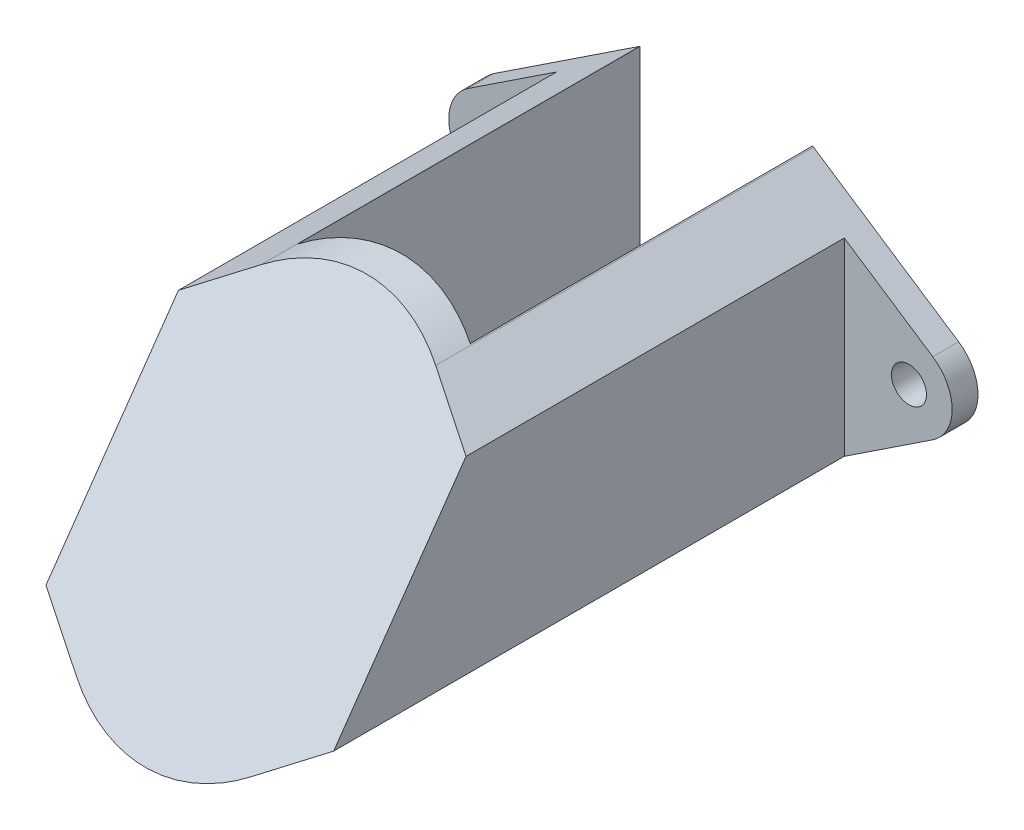
SolidWorks part; units mm, degrees
ref_plane "Front Plane" through (0, 0, 0) normal (0, 0, 1) x (1, 0, 0)
ref_plane "Top Plane" through (0, 0, 0) normal (0, 1, 0) x (1, 0, 0)
ref_plane "Right Plane" through (0, 0, 0) normal (1, 0, 0) x (0, 0, -1)
sketch "Sketch1" plane through (0, 0, 0) normal (0, 0, 1) x (1, 0, 0)
  line L0 (-14.5, 0) -> (14.5, 0) construction
  line L1 (-16.1552, 2.5021) -> (-6.069, 9.1743)
  line L2 (6.069, 9.1743) -> (16.1552, 2.5021)
  line L5 (16.1552, -2.5021) -> (6.069, -9.1743)
  line L6 (-6.069, -9.1743) -> (-16.1552, -2.5021)
  arc A0 (-6.069, -9.1743) -> (6.069, -9.1743) centre (0, 0) ccw
  arc A1 (16.1552, -2.5021) -> (16.1552, 2.5021) centre (14.5, 0) ccw
  arc A2 (-16.1552, 2.5021) -> (-16.1552, -2.5021) centre (-14.5, 0) ccw
  arc A3 (6.069, 9.1743) -> (-6.069, 9.1743) centre (0, 0) ccw
  point P1 (0, 0)
  point P4 (0, 0)
  point P6 (16.1552, -2.5021)
  dimension "D1" = 6
  dimension "D2" = 22
  dimension "D3" = 29
extrude "Boss-Extrude1" add sketch "Sketch1" along normal blind 45
sketch "Sketch3" plane through (0, 0, 0) normal (1, 0, 0) x (0, 0, -1)
  line L0 (-25, 11) -> (-40.4046, -11)
  line L1 (0, 11) -> (-45, 11) construction
  line L2 (-45, -11) -> (0, -11) construction
  line L3 (-40.4046, -11) -> (0, -11)
  line L4 (0, -11) -> (0, 11)
  line L5 (0, 11) -> (-25, 11)
  point P6 (-2.9931, 11)
  dimension "D1" = 35
  dimension "D2" = 25
extrude "Cut-Extrude1" cut sketch "Sketch3" against normal through all both and the other way through all flip side to cut
sketch "Sketch5" plane through (0, 0, 0) normal (0, 0, -1) x (-1, 0, 0)
  line L1 (-10, -12.207) -> (10, -12.207)
  line L2 (-10, -12.207) -> (-10, 12.207)
  line L3 (-10, 12.207) -> (10, 12.207)
  line L4 (10, -12.207) -> (10, 12.207)
  line L5 (-10, -12.207) -> (10, 12.207) construction
  line L6 (-10, 12.207) -> (10, -12.207) construction
  point P0 (0, 0)
  dimension "D1" = 20
extrude "Cut-Extrude2" cut sketch "Sketch5" against normal through all from offset 1.8 flip side to cut offset against normal yes
hole_wizard "#2 Clearance Hole1" positions "Sketch6" profile "Sketch7" hole size "#2" standard "ANSI Inch" end condition through all
sketch "Sketch6" plane through (0, 0, 1.8) normal (0, 0, 1) x (1, 0, 0)
  arc A0 (16.1552, -2.5021) -> (16.1552, 2.5021) centre (14.5, 0) ccw construction
  arc A1 (-16.1552, 2.5021) -> (-16.1552, -2.5021) centre (-14.5, 0) ccw construction
  point P0 (14.5, 0)
  point P2 (-14.5, 0)
  point P5 (0, 0)
  point P9 (0, 0)
sketch "Sketch7" plane through (14.5, 0, 1.8) normal (1, 0, 0) x (0, -1, 0)
  line L0 (0, 0) -> (0, 1.8)
  line L1 (0, 1.8) -> (1.2192, 1.8)
  line L2 (1.2192, 1.8) -> (1.2192, 0)
  line L5 (1.2192, 0) -> (0, 0)
  line L11 (0, -6.35) -> (0, 107.95) construction
  dimension "Thru Hole Dia." = 2.4384
  dimension "Thru Hole Depth" = 1.8
sketch "Sketch8" plane through (0, 15.365, 21.9436) normal (0, 0.5736, 0.8192) x (1, 0, 0)
  line L0 (-10, -10.7321) -> (-10, -26.7824) construction
  line L1 (6, 32.1858) -> (-6, 32.1858)
  line L2 (6, 32.1858) -> (6, -32.1858)
  line L3 (6, -32.1858) -> (-6, -32.1858)
  line L4 (-6, 32.1858) -> (-6, -32.1858)
  line L5 (6, 32.1858) -> (-6, -32.1858) construction
  line L6 (6, -32.1858) -> (-6, 32.1858) construction
  ellipse E0 centre (0, -18.7573) end of major axis (0, -32.1858) minor radius 11 (-6.069, -29.957) -> (6.069, -29.957) ccw construction
  point P0 (0, 0)
  dimension "D1" = 4
extrude "Cut-Extrude3" cut sketch "Sketch8" against normal through all from offset 2
